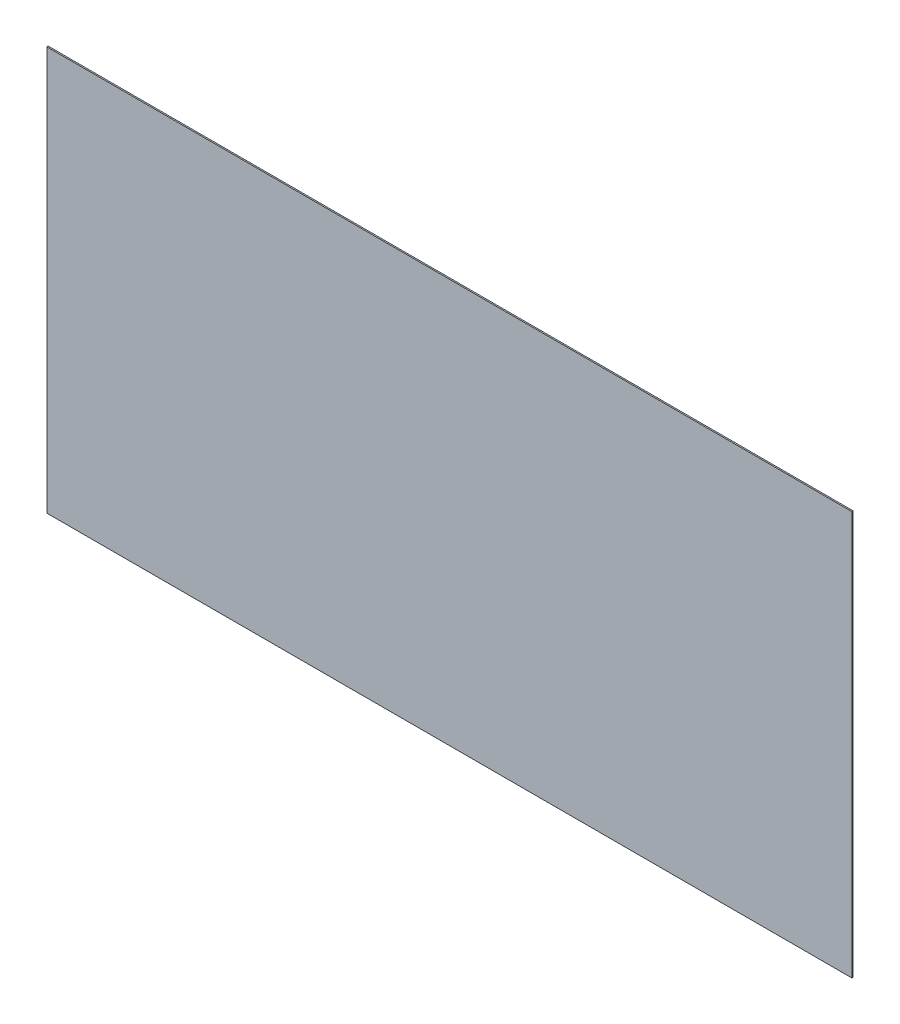
SolidWorks part; units mm, degrees
ref_plane "Front Plane" through (0, 0, 0) normal (0, 0, 1) x (1, 0, 0)
ref_plane "Top Plane" through (0, 0, 0) normal (0, 1, 0) x (1, 0, 0)
ref_plane "Right Plane" through (0, 0, 0) normal (1, 0, 0) x (0, 0, -1)
other "Configuration Table"
sketch "Sketch1" plane through (0, 0, 0) normal (0, 0, 1) x (1, 0, 0)
  line L1 (0, 0) -> (618, 0)
  line L2 (0, 0) -> (0, 310)
  line L3 (0, 310) -> (618, 310)
  line L4 (618, 0) -> (618, 310)
extrude "CEK_1L_on_ic_sac_1.0_1" add sketch "Sketch1" along normal blind 1 separate body
